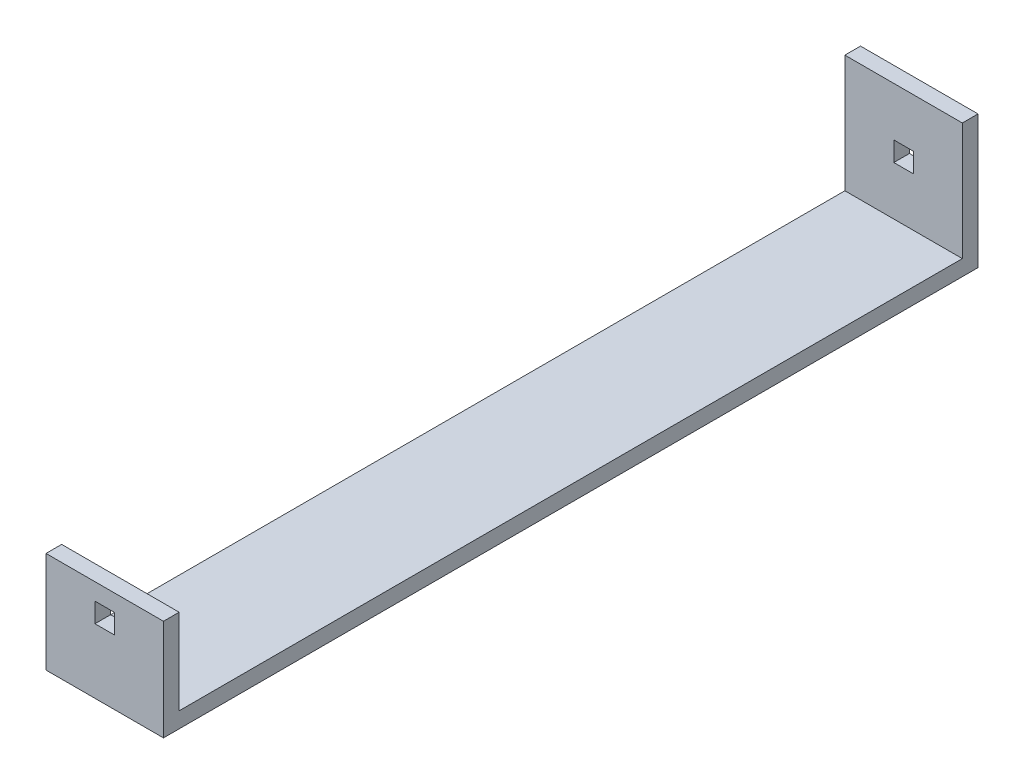
SolidWorks part; units mm, degrees
ref_plane "Front Plane" through (0, 0, 0) normal (0, 0, 1) x (1, 0, 0)
ref_plane "Top Plane" through (0, 0, 0) normal (0, 1, 0) x (1, 0, 0)
ref_plane "Right Plane" through (0, 0, 0) normal (1, 0, 0) x (0, 0, -1)
sketch "Sketch1" plane through (0, 0, 0) normal (0, 1, 0) x (1, 0, 0)
  line L0 (-75, 520) -> (75, 520)
  line L1 (-75, -500) -> (75, -500)
  line L2 (-75, -500) -> (-75, 500)
  line L3 (-75, 500) -> (75, 500)
  line L4 (75, -500) -> (75, 500)
  line L5 (-75, -500) -> (75, 500) construction
  line L6 (-75, 500) -> (75, -500) construction
  line L7 (-75, -520) -> (75, -520)
  point P0 (0, 0)
sketch "Sketch2" plane through (0, 0, 0) normal (0, 1, 0) x (1, 0, 0)
  line L0 (-75, -520) -> (75, -520) construction
  line L1 (-75, 520) -> (75, 520) construction
  line L2 (-75, -500) -> (-75, 500) construction
  line L4 (75, -500) -> (75, 500) construction
  line L6 (-75, -520) -> (75, -520)
  line L7 (-75, 520) -> (75, 520)
  line L8 (-75, -520) -> (-75, 520)
  line L10 (75, -520) -> (75, 520)
extrude "Boss-Extrude1" add sketch "Sketch2" against normal blind 20
sketch "Sketch3" plane through (0, 0, 0) normal (0, 1, 0) x (1, 0, 0)
  line L0 (75, -520) -> (75, 520) construction
  line L1 (-75, 520) -> (-75, -520) construction
  line L2 (-75, -520) -> (75, -520) construction
  line L3 (-75, 520) -> (75, 520) construction
  line L4 (-75, 500) -> (75, 500) construction
  line L6 (-75, -500) -> (75, -500) construction
  line L8 (75, -520) -> (75, -500)
  line L9 (-75, 520) -> (-75, 500)
  line L10 (-75, -520) -> (75, -520)
  line L11 (-75, 520) -> (75, 520)
  line L12 (-75, 500) -> (75, 500)
  line L14 (-75, -500) -> (75, -500)
  line L16 (75, 500) -> (75, 520)
  line L17 (-75, -500) -> (-75, -520)
extrude "Boss-Extrude2" add sketch "Sketch3" along normal blind 150
sketch "Sketch4" plane through (0, 0, 520) normal (0, 0, 1) x (1, 0, 0)
  line L0 (75, -20) -> (75, 150) construction
  line L1 (-12.5, 62.5) -> (12.5, 62.5)
  line L2 (-12.5, 62.5) -> (-12.5, 87.5)
  line L3 (-12.5, 87.5) -> (12.5, 87.5)
  line L4 (12.5, 62.5) -> (12.5, 87.5)
  line L5 (-12.5, 62.5) -> (12.5, 87.5) construction
  line L6 (-12.5, 87.5) -> (12.5, 62.5) construction
  line L7 (75, 0) -> (75, 150) construction
  line L8 (-75, 0) -> (75, 0) construction
  line L9 (-75, 0) -> (75, 0) construction
  point P0 (0, 75)
  point P11 (75, 75)
  dimension "D1" = 25
extrude "Cut-Extrude1" cut sketch "Sketch4" against normal through all both and the other way through all
sketch "Sketch5" plane through (0, -20, 0) normal (0, -1, 0) x (1, 0, 0)
  line L0 (0, 500) -> (0, 520) construction
  line L1 (-55, -500) -> (55, -500) construction
  line L2 (-55, -500) -> (-55, 500) construction
  line L3 (-55, 500) -> (55, 500) construction
  line L4 (55, -500) -> (55, 500) construction
  line L5 (-55, -500) -> (55, 500) construction
  line L6 (-55, 500) -> (55, -500) construction
  line L7 (-75, 520) -> (75, 520) construction
  line L8 (55, 0) -> (75, 0) construction
  line L9 (75, 520) -> (75, -520) construction
  circle A0 centre (-55, 500) radius 6
  circle A1 centre (55, 500) radius 6
  circle A2 centre (-55, -500) radius 6
  circle A3 centre (55, -500) radius 6
  point P0 (0, 0)
  dimension "D2" = 12
  dimension "D1" = 20
extrude "Boss-Extrude3" add sketch "Sketch5" along normal blind 10
sketch "Sketch6" plane through (0, 0, 520) normal (0, 0, 1) x (1, 0, 0)
  line L0 (75, -20) -> (75, 150) construction
  line L1 (-75, 150) -> (75, 150)
  line L2 (-75, 150) -> (-75, 109)
  line L3 (-75, 109) -> (75, 109)
  line L4 (75, 150) -> (75, 109)
  dimension "D1" = 41
extrude "Cut-Extrude2" cut sketch "Sketch6" against normal up to next
